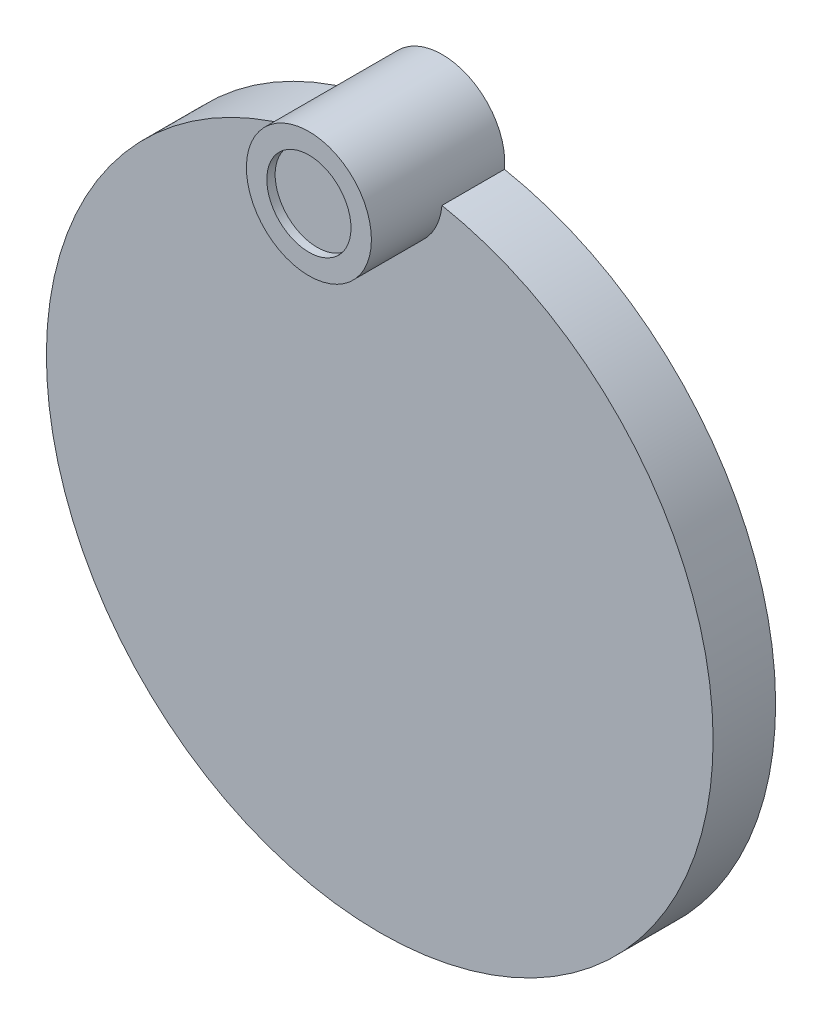
SolidWorks part; units mm, degrees
ref_plane "正面" through (0, 0, 0) normal (0, 0, 1) x (1, 0, 0)
ref_plane "平面" through (0, 0, 0) normal (0, 1, 0) x (1, 0, 0)
ref_plane "右側面" through (0, 0, 0) normal (1, 0, 0) x (0, 0, -1)
sketch "ｽｹｯﾁ4" plane through (0, 0, 0) normal (0, 0, 1) x (1, 0, 0)
  arc A1 (-14.9339, -1.4063) -> (9.9804, -0.625) centre (0, -80) ccw
  arc A3 (14.9339, -1.4063) -> (-14.9339, -1.4063) centre (0, 0) ccw
  dimension "D4" = 30
  dimension "D2" = 80
extrude "ﾎﾞｽ - 押し出し1" add sketch "ｽｹｯﾁ4" along normal blind 15
sketch "ｽｹｯﾁ5" plane through (0, 0, 15) normal (0, 0, 1) x (1, 0, 0)
  circle A0 centre (0, 0) radius 15
  dimension "D1" = 30
extrude "ﾎﾞｽ - 押し出し3" add sketch "ｽｹｯﾁ5" along normal blind 17
sketch "ｽｹｯﾁ9" plane through (0, 0, 32) normal (0, 0, 1) x (1, 0, 0)
  circle A0 centre (0, 0) radius 10.1
  dimension "D1" = 20.2
extrude "ｶｯﾄ - 押し出し2" cut sketch "ｽｹｯﾁ9" against normal blind 2
